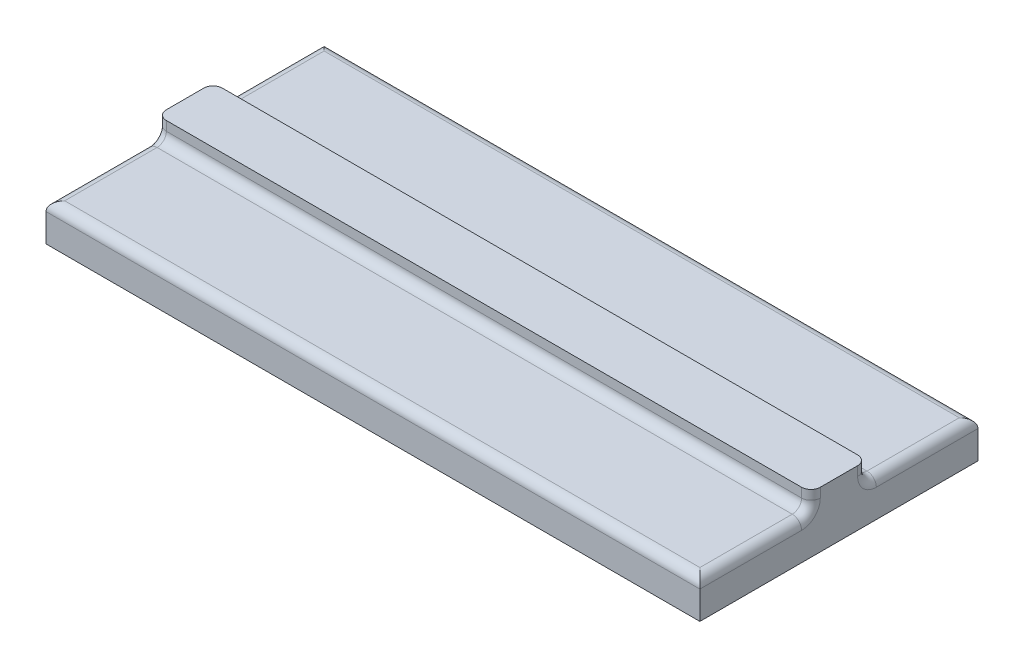
SolidWorks part; units mm, degrees
ref_plane "Alzado" through (0, 0, 0) normal (0, 0, 1) x (1, 0, 0)
ref_plane "Planta" through (0, 0, 0) normal (0, 1, 0) x (1, 0, 0)
ref_plane "Vista lateral" through (0, 0, 0) normal (1, 0, 0) x (0, 0, -1)
sketch "Croquis1" plane through (0, 0, 0) normal (1, 0, 0) x (0, 0, -1)
  line L0 (0, 0) -> (0, 25.5344) construction
  line L5 (74.4275, 0) -> (-74.4275, 0)
  line L6 (-74.4275, 0) -> (-74.4275, 20)
  line L11 (74.4275, 0) -> (74.4275, 20)
  line L12 (-74.4275, 20) -> (-15, 20)
  line L13 (74.4275, 20) -> (15, 20)
  line L14 (-15, 20) -> (-15, 30)
  line L15 (15, 20) -> (15, 30)
  line L16 (-15, 30) -> (15, 30)
  point P11 (0, 30)
  dimension "D1" = 20
  dimension "D2" = 10
  dimension "D3" = 30
extrude "Saliente-Extruir1" add sketch "Croquis1" along normal mid plane 350
fillet "Redondeo1" radius 5 12 edges at (175, 25, -15) (-175, 25, -15) (175, 25, 15) (-175, 25, 15) (0, 20, -74.4275) (175, 20, -44.7137) (0, 20, -15) (-175, 20, -44.7137) (0, 20, 15) (175, 20, 44.7137) (0, 20, 74.4275) (-175, 20, 44.7137)
